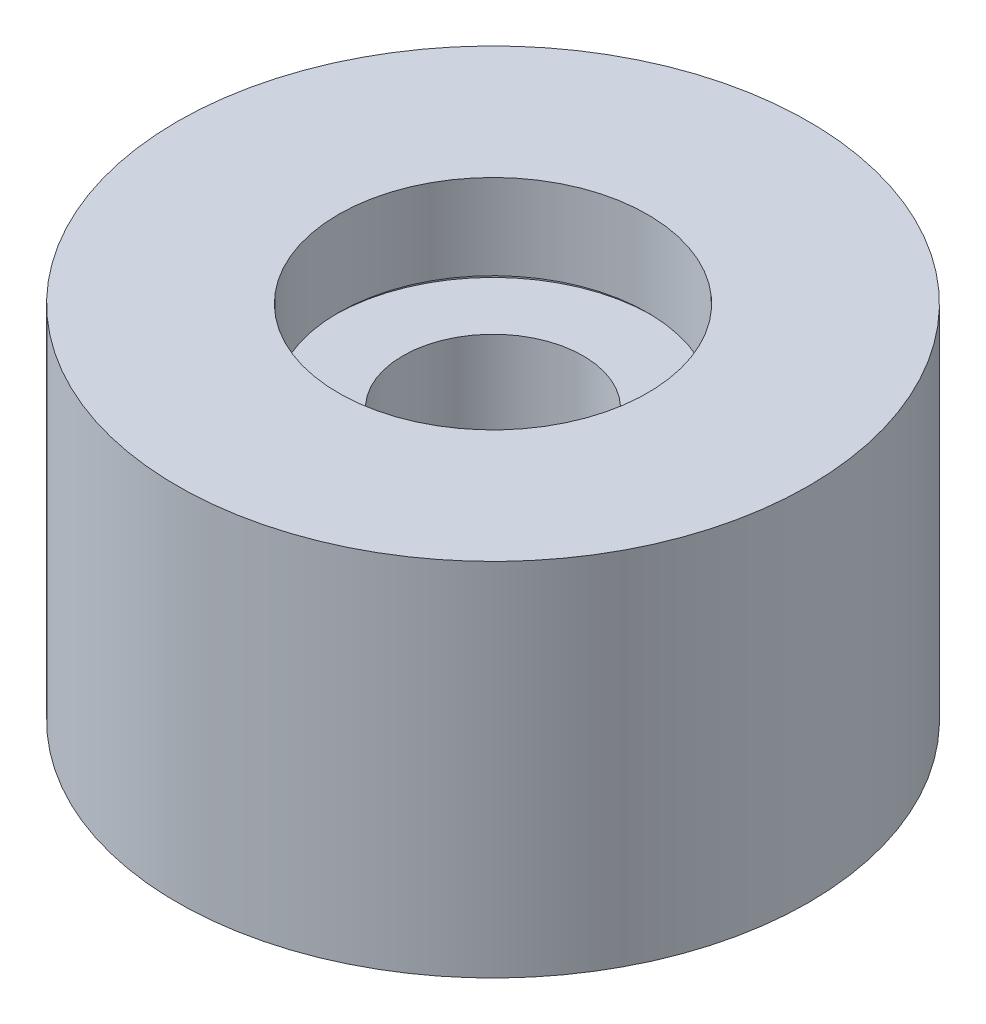
SolidWorks part; units mm, degrees
ref_plane "Płaszczyzna przednia" through (0, 0, 0) normal (0, 0, 1) x (1, 0, 0)
ref_plane "Płaszczyzna górna" through (0, 0, 0) normal (0, 1, 0) x (1, 0, 0)
ref_plane "Płaszczyzna prawa" through (0, 0, 0) normal (1, 0, 0) x (0, 0, -1)
sketch "Szkic1" plane through (0, 0, 0) normal (0, 0, 1) x (1, 0, 0)
  line L0 (0, 104.9746) -> (0, -35.0254) construction
  line L1 (-122.5, 104.9746) -> (-122.5, -35.0254)
  line L2 (-60, 104.9746) -> (-60, 71.9746)
  line L3 (-60, 104.9746) -> (-122.5, 104.9746)
  line L4 (-60, -35.0254) -> (-122.5, -35.0254)
  line L5 (-60, 104.9746) -> (-60, 69.9746)
  line L6 (-60, 69.9746) -> (-35, 69.9746)
  line L7 (-35, 69.9746) -> (-35, -35.0254)
  line L8 (-35, -35.0254) -> (-60, -35.0254)
  line L9 (-60, 69.9746) -> (-62, 69.9746)
  line L10 (-62, 69.9746) -> (-62, 71.9746)
  line L11 (-62, 71.9746) -> (-60, 71.9746)
  dimension "D1" = 122.5
  dimension "D2" = 60
  dimension "D3" = 35
  dimension "D4" = 140
revolve "Obrót1" add sketch "Szkic1" angle 360 about L0
